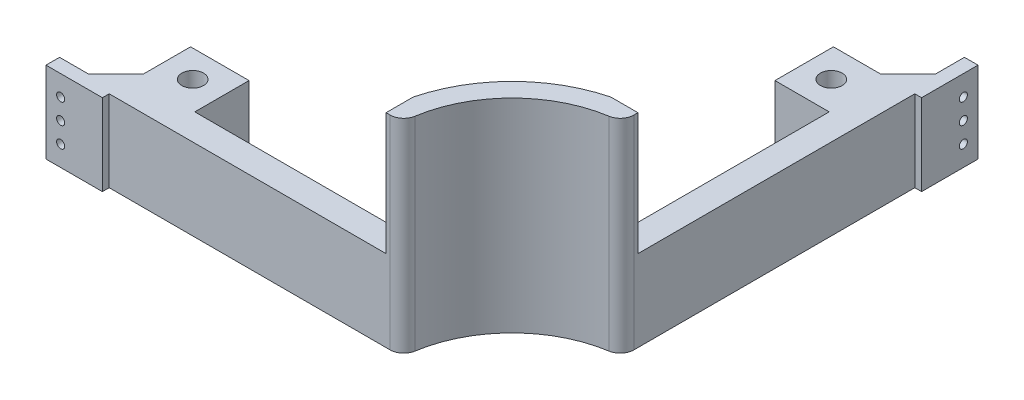
SolidWorks part; units mm, degrees
ref_plane "Front Plane" through (0, 0, 0) normal (0, 0, 1) x (1, 0, 0)
ref_plane "Top Plane" through (0, 0, 0) normal (0, 1, 0) x (1, 0, 0)
ref_plane "Right Plane" through (0, 0, 0) normal (1, 0, 0) x (0, 0, -1)
sketch "Sketch2" plane through (0, 0, 0) normal (0, 1, 0) x (1, 0, 0)
  line L0 (0, 0) -> (0, 41) construction
  line L1 (0, 0) -> (-41, 0) construction
  line L2 (-2.5, 47.4104) -> (-2.5, 49.4444)
  line L3 (-47.4104, 2.5) -> (-49.4444, 2.5)
  line L4 (-2.5, 49.4444) -> (-2.5, 151)
  line L5 (-49.4444, 2.5) -> (-151, 2.5)
  line L21 (0, 0) -> (-64.3582, 64.3582) construction
  line L44 (-129.4444, 12.5) -> (-48.9285, 12.5)
  line L45 (-12.5, 129.4444) -> (-12.5, 48.9285)
  line L46 (-129.4444, 12.5) -> (-129.4444, 32.5)
  line L47 (-129.4444, 32.5) -> (-151, 32.5)
  line L48 (-151, 32.5) -> (-151, 15)
  line L49 (-161, 5) -> (-171.7957, 5)
  line L50 (-171.7957, 5) -> (-171.7957, 0)
  line L51 (-171.7957, 0) -> (-151, 0)
  line L52 (-151, 0) -> (-151, 2.5)
  line L53 (-151, 15) -> (-161, 5)
  line L54 (0, 151) -> (-2.5, 151)
  line L55 (0, 171.7957) -> (0, 151)
  line L56 (-5, 171.7957) -> (0, 171.7957)
  line L57 (-5, 161) -> (-5, 171.7957)
  line L58 (-15, 151) -> (-5, 161)
  line L59 (-32.5, 151) -> (-15, 151)
  line L60 (-32.5, 129.4444) -> (-32.5, 151)
  line L61 (-12.5, 129.4444) -> (-32.5, 129.4444)
  line L62 (-22.5, 129.4444) -> (-22.5, 151) construction
  arc A0 (-6.7188, 42.4719) -> (-42.4719, 6.7187) centre (0, 0) ccw
  arc A1 (-47.4104, 2.5) -> (-42.4719, 6.7187) centre (-47.4104, 7.5) ccw
  arc A2 (-6.7188, 42.4719) -> (-2.5, 47.4104) centre (-7.5, 47.4104) ccw
  arc A5 (-6.7188, 42.4719) -> (-42.4719, 6.7187) centre (0, 0) ccw
  arc A6 (-12.5, 48.9285) -> (-48.9285, 12.5) centre (0, 0) ccw
  circle A7 centre (0, 0) radius 41 construction
  circle A8 centre (-22.5, 140.2222) radius 4
  circle A9 centre (-140.2222, 22.5) radius 4
  point P12 (-2.5, 42.9273)
  point P18 (-151, 5)
  dimension "D1" = 86
  dimension "D2" = 8
  dimension "D5" = 5
  dimension "D6" = 5
  dimension "D7" = 110
  dimension "D10" = 7.5
  dimension "D3" = 5
  dimension "D4" = 5
  dimension "D8" = 10
  dimension "D9" = 10
  dimension "D11" = 2.5
  dimension "D12" = 5
  dimension "D14" = 110
extrude "Boss-Extrude1" add sketch "Sketch2" along normal blind 30 contours L45 A6 L44 L46 L47 L48 L53 L49 L50 L51 L52 L5 L3 A1 A0 A2 L2 L4 L54 L55 L56 L57 L58 L59 L60 L61
sketch "Sketch10" plane through (-5, 0, 0) normal (-1, 0, 0) x (0, 0, 1)
  line L0 (-166.3979, 30) -> (-166.3979, 0) construction
  line L1 (-161, 30) -> (-171.7957, 30) construction
  line L2 (-161, 0) -> (-171.7957, 0) construction
  line L3 (-171.7957, 15) -> (-161, 15) construction
  line L4 (-171.7957, 30) -> (-171.7957, 0) construction
  line L5 (-161, 30) -> (-161, 0) construction
  line L6 (-171.7957, 22.5) -> (-161, 22.5) construction
  line L7 (-171.7957, 7.5) -> (-161, 7.5) construction
  circle A0 centre (-166.3979, 22.5) radius 1.5
  circle A1 centre (-166.3979, 15) radius 1.5
  circle A2 centre (-166.3979, 7.5) radius 1.5
  dimension "D3" = 3
  dimension "D1" = 7.5
  dimension "D2" = 7.5
extrude "Cut-Extrude1" cut sketch "Sketch10" against normal blind 10
sketch "Sketch11" plane through (0, 0, -5) normal (0, 0, -1) x (-1, 0, 0)
  line L0 (166.3979, 0) -> (166.3979, 30) construction
  line L1 (161, 0) -> (171.7957, 0) construction
  line L2 (161, 30) -> (171.7957, 30) construction
  line L3 (171.7957, 15) -> (161, 15) construction
  line L4 (171.7957, 30) -> (171.7957, 0) construction
  line L5 (161, 30) -> (161, 0) construction
  line L6 (171.7957, 7.5) -> (161, 7.5) construction
  line L7 (171.7957, 22.5) -> (161, 22.5) construction
  circle A0 centre (166.3979, 22.5) radius 1.5
  circle A1 centre (166.3979, 15) radius 1.5
  circle A2 centre (166.3979, 7.5) radius 1.5
  dimension "D3" = 3
  dimension "D1" = 7.5
  dimension "D2" = 7.5
extrude "Cut-Extrude3" cut sketch "Sketch11" against normal blind 10
sketch "Sketch13" plane through (0, 30, 0) normal (0, 1, 0) x (1, 0, 0)
  line L0 (-48.9285, 12.5) -> (-48.9285, 2.5)
  line L1 (-47.4104, 2.5) -> (-151, 2.5) construction
  line L2 (-12.5, 48.9285) -> (-2.5, 48.9285)
  line L3 (-2.5, 47.4104) -> (-2.5, 151) construction
  line L4 (-47.4104, 2.5) -> (-48.9285, 2.5)
  line L5 (-2.5, 47.4104) -> (-2.5, 48.9285)
  arc A0 (-47.4104, 2.5) -> (-42.4719, 6.7188) centre (-47.4104, 7.5) ccw construction
  arc A1 (-6.7187, 42.4719) -> (-2.5, 47.4104) centre (-7.5, 47.4104) ccw construction
  arc A2 (-6.7187, 42.4719) -> (-42.4719, 6.7188) centre (0, 0) ccw construction
  arc A3 (-12.5, 48.9285) -> (-48.9285, 12.5) centre (0, 0) ccw construction
  arc A4 (-47.4104, 2.5) -> (-42.4719, 6.7188) centre (-47.4104, 7.5) ccw
  arc A5 (-6.7187, 42.4719) -> (-2.5, 47.4104) centre (-7.5, 47.4104) ccw
  arc A6 (-6.7187, 42.4719) -> (-42.4719, 6.7188) centre (0, 0) ccw
  arc A7 (-12.5, 48.9285) -> (-48.9285, 12.5) centre (0, 0) ccw
extrude "Boss-Extrude2" add sketch "Sketch13" along normal blind 45 contours L5 L2 A7 L0 L4 A4 A6 A5
